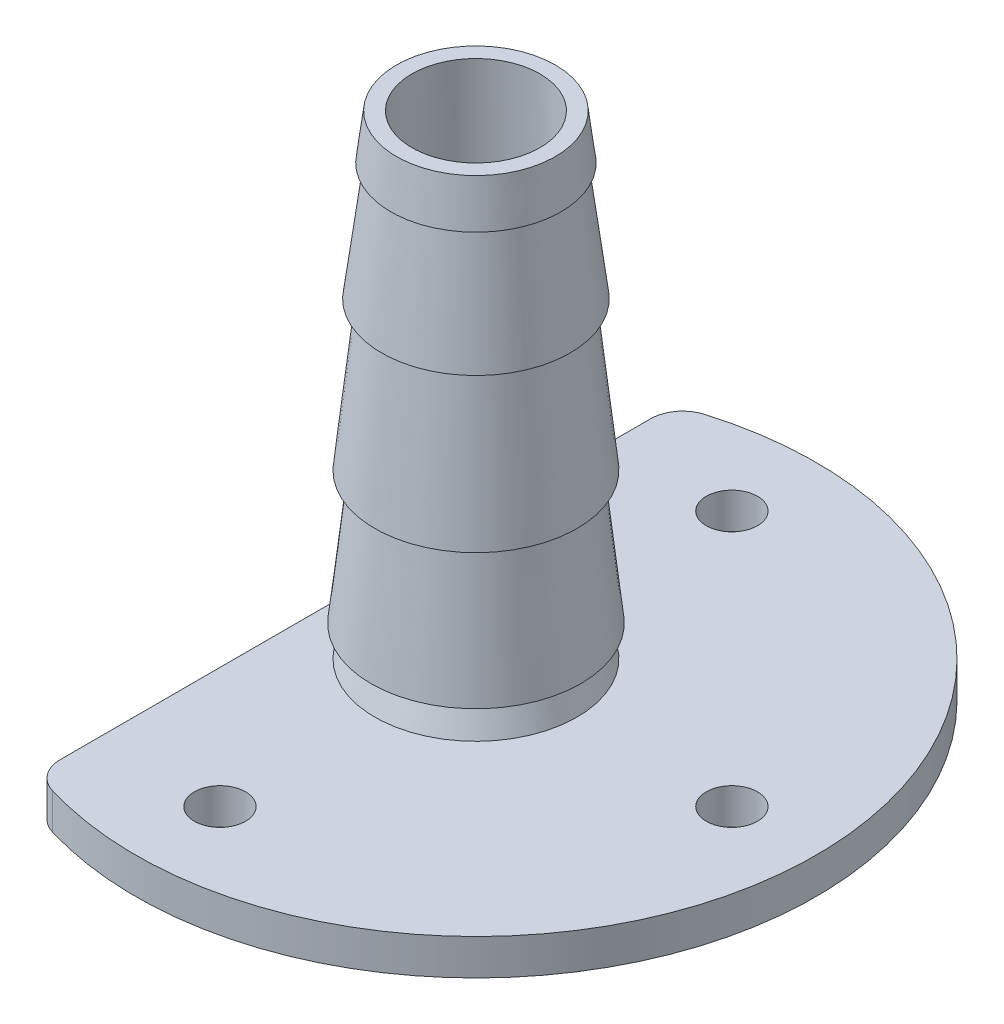
SolidWorks part; units mm, degrees
ref_plane "前视基准面" through (0, 0, 0) normal (0, 0, 1) x (1, 0, 0)
ref_plane "上视基准面" through (0, 0, 0) normal (0, 1, 0) x (1, 0, 0)
ref_plane "右视基准面" through (0, 0, 0) normal (1, 0, 0) x (0, 0, -1)
sketch "草图1" plane through (0, 0, 0) normal (0, 0, 1) x (1, 0, 0)
  line L0 (0, 0) -> (4.6, 0) construction
  line L1 (5.2651, 0) -> (21.2651, 0)
  line L3 (0, 0) -> (0, 31.9096) construction
  line L4 (0, 31.9096) -> (4.0017, 31.9096) construction
  line L5 (4.0017, 31.9096) -> (4.9639, 31.9096)
  line L6 (4.9639, 31.9096) -> (5.3158, 29.093)
  line L7 (5.3158, 29.093) -> (4.9639, 29.093)
  line L13 (4.5572, 2.2838) -> (4.0017, 31.9096)
  line L14 (0, 12.4547) -> (6.3219, 12.4547) construction
  line L16 (4.9639, 29.093) -> (5.8946, 21.7433)
  line L17 (5.8946, 21.7433) -> (5.3158, 21.7433)
  line L18 (5.3158, 21.7433) -> (6.3219, 12.4547)
  line L19 (6.3219, 12.4547) -> (5.6598, 12.4547)
  line L22 (4.6744, 1.6456) -> (5.2651, 0)
  line L24 (8.0344, 2.2447) -> (14.3, 2.2447)
  line L28 (8.0344, 2.2447) -> (6.3219, 2.2447)
  line L30 (6.3219, 2.2447) -> (5.6298, 4.173)
  line L31 (5.6598, 12.4547) -> (6.5568, 4.173)
  line L32 (6.5568, 4.173) -> (5.6298, 4.173)
  line L33 (14.3, 2.2447) -> (21.2651, 2.2447)
  line L34 (21.2651, 2.2447) -> (21.2651, 0)
  arc A0 (4.6744, 1.6456) -> (4.5572, 2.2838) centre (6.5568, 2.3213) cw
  dimension "D1" = 2
revolve "旋转1" add sketch "草图1" angle 360 about L3
sketch "草图2" plane through (0, 0, 0) normal (0, -1, 0) x (1, 0, 0)
  circle A0 centre (0, 0) radius 16 construction
  circle A1 centre (-16, 0) radius 1.6
  circle A2 centre (0, -16) radius 1.6
  circle A3 centre (16, 0) radius 1.6
  circle A4 centre (0, 16) radius 1.6
extrude "切除-拉伸1" cut sketch "草图2" against normal blind 10
sketch "草图3" plane through (0, 2.2447, 0) normal (0, 1, 0) x (1, 0, 0)
  line L0 (-7.532, -19.8865) -> (-7.532, 19.8865)
  circle A0 centre (0, 0) radius 21.2651 construction
  circle A1 centre (0, 0) radius 21.2651
  circle M2 centre (-16, 0) radius 1.6
  circle M6 centre (0, 0) radius 21.2651
extrude "切除-拉伸2" cut sketch "草图3" against normal blind 10 contours L0 M6 M2
fillet "圆角1" radius 2 2 edges at (-7.532, 1.1224, 19.8865) (-7.532, 1.1224, -19.8865)
